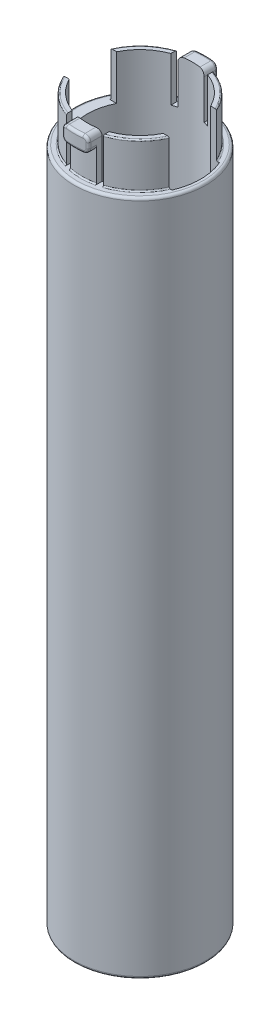
SolidWorks part; units mm, degrees
material "1023 碳钢板 (SS)"
ref_plane "前视基准面" through (0, 0, 0) normal (0, 0, 1) x (1, 0, 0)
ref_plane "上视基准面" through (0, 0, 0) normal (0, 1, 0) x (1, 0, 0)
ref_plane "右视基准面" through (0, 0, 0) normal (1, 0, 0) x (0, 0, -1)
sketch "草图6" plane through (0, 0, 0) normal (0, 1, 0) x (1, 0, 0)
  circle A0 centre (0, 0) radius 12.5
extrude "凸台-拉伸2" add sketch "草图6" along normal mid plane 137
sketch "草图7" plane through (0, 68.5, 0) normal (0, 1, 0) x (1, 0, 0)
  circle A2 centre (0, 0) radius 10
extrude "切除-拉伸3" cut sketch "草图7" against normal blind 80
sketch "草图8" plane through (0, 68.5, 0) normal (0, 1, 0) x (1, 0, 0)
  line L0 (8.9303, 4.5) -> (10.583, 4.5)
  line L7 (8.9303, -4.5) -> (10.583, -4.5)
  circle A1 centre (0, 0) radius 10 construction
  arc A2 (8.9303, -4.5) -> (8.9303, 4.5) centre (0, 0) ccw
  arc A3 (10.583, -4.5) -> (10.583, 4.5) centre (0, 0) ccw
extrude "切除-拉伸5" cut sketch "草图8" against normal blind 80
sketch "草图9" plane through (0, 68.5, 0) normal (0, 1, 0) x (1, 0, 0)
  circle A0 centre (0, 0) radius 11
  circle A1 centre (0, 0) radius 12.5 construction
  circle A2 centre (0, 0) radius 12.5
extrude "切除-拉伸6" cut sketch "草图9" against normal blind 8.5
sketch "草图10" plane through (0, 68.5, 0) normal (0, 1, 0) x (1, 0, 0)
  line L1 (8.9303, -4.5) -> (10.0374, -4.5) construction
  line L3 (-10.0374, -4.5) -> (-8.9303, -4.5)
  line L5 (-8.9303, 4.5) -> (-10.0374, 4.5)
  arc A0 (10.0374, 4.5) -> (10.0374, -4.5) centre (0, 0) ccw construction
  arc A1 (8.9303, 4.5) -> (8.9303, -4.5) centre (0, 0) ccw construction
  arc A2 (-10.0374, 4.5) -> (-10.0374, -4.5) centre (0, 0) ccw
  arc A3 (-8.9303, 4.5) -> (-8.9303, -4.5) centre (0, 0) ccw
extrude "切除-拉伸7" cut sketch "草图10" against normal blind 8.5
ref_plane "卡扣底面" through (0, 0, 10) normal (0, 0, 1) x (1, 0, 0)
sketch "草图11" plane through (0, 0, 10) normal (0, 0, 1) x (1, 0, 0)
  line L3 (-2.5, 68.5) -> (2.5, 68.5)
  line L4 (-2.5, 68.5) -> (-2.5, 65.5)
  line L5 (-2.5, 65.5) -> (2.5, 65.5)
  line L6 (2.5, 68.5) -> (2.5, 65.5)
extrude "凸台-拉伸3" add sketch "草图11" along normal up to surface (2.2474 mm away)
mirror "镜向1" about plane through (0, 0, 0) normal (0, 0, 1) of "凸台-拉伸3"
sketch "草图13" plane through (0, 68.5, 0) normal (0, 1, 0) x (1, 0, 0)
  line L0 (2.5, -10.7121) -> (2.5, 10.7121)
  line L1 (2.5, 10.7121) -> (3.5, 10.7121)
  line L2 (3.5, 10.7121) -> (3.5, -10.7121)
  line L3 (3.5, -10.7121) -> (2.5, -10.7121)
  line L5 (-3.5, 10.7121) -> (-3.5, -10.7121)
  line L6 (-2.5, 10.7121) -> (-3.5, 10.7121)
  line L7 (-2.5, -10.7121) -> (-2.5, 10.7121)
  line L8 (-3.5, -10.7121) -> (-2.5, -10.7121)
extrude "切除-拉伸8" cut sketch "草图13" against normal blind 8.5
fillet "圆角1" radius 1 8 edges at (2.5, 65.5, -11.4798) (-2.5, 65.5, -11.4798) (2.5, 68.5, -10.965) (-2.5, 68.5, -10.965) (-2.5, 65.5, 11.4798) (-2.5, 68.5, 10.965) (2.5, 65.5, 11.4798) (2.5, 68.5, 10.965)
sketch "草图14" plane through (0, -68.5, 0) normal (0, -1, 0) x (-1, 0, 0)
  circle A0 centre (0, 0) radius 9.5
extrude "切除-拉伸9" cut sketch "草图14" against normal blind 3
fillet "圆角2" radius 0.5 16 edges at (-2.1288, 68.2776, 12.3174) (-2.5, 67, 12.2474) (-2.2876, 65.8838, 12.2889) (0, 65.5, 12.5) (2.1288, 65.7224, 12.3174) (2.5, 67, 12.2474) (2.2876, 68.1162, 12.2889) (0, 68.5, -12.5) (-2.2876, 68.1162, -12.2889) (-2.5, 67, -12.2474) (-2.1288, 65.7224, -12.3174) (0, 65.5, -12.5) (2.2876, 65.8838, -12.2889) (2.5, 67, -12.2474) (0, 68.5, 12.5) (2.1288, 68.2776, -12.3174)
sketch "草图15" plane through (0, -65.5, 0) normal (0, -1, 0) x (-1, 0, 0)
  circle A0 centre (0, 0) radius 8
extrude "切除-拉伸10" cut sketch "草图15" against normal through all
sketch "草图16" plane through (0, -11.5, 0) normal (0, 1, 0) x (1, 0, 0)
  line L0 (10.583, 4.5) -> (8.9303, 4.5) construction
  line L1 (8.9303, -4.5) -> (10.583, -4.5) construction
  line L2 (10.583, 4.5) -> (6.6144, 4.5)
  line L3 (6.6144, -4.5) -> (10.583, -4.5)
  arc A0 (10.583, -4.5) -> (10.583, 4.5) centre (0, 0) ccw construction
  arc A1 (10.583, -4.5) -> (10.583, 4.5) centre (0, 0) ccw
  circle A2 centre (0, 0) radius 8 construction
  arc A3 (6.6144, -4.5) -> (6.6144, 4.5) centre (0, 0) ccw
extrude "切除-拉伸11" cut sketch "草图16" against normal blind 5
fillet "圆角3" radius 0.5 5 edges at (0, -68.5, 12.5) (0, -68.5, -9.5) (0, -65.5, -9.5) (0, -65.5, -8) (0, 60, 12.5)
fillet "圆角4" radius 0.25 2 edges at (-7.3893, 68.5, 8.1485) (-7.3893, 68.5, -8.1485)
fillet "圆角6" radius 0.25 6 edges at (7.3893, 60, 8.1485) (0, 60, 11) (-7.3893, 60, 8.1485) (-7.3893, 60, -8.1485) (0, 60, -11) (7.3893, 60, -8.1485)
